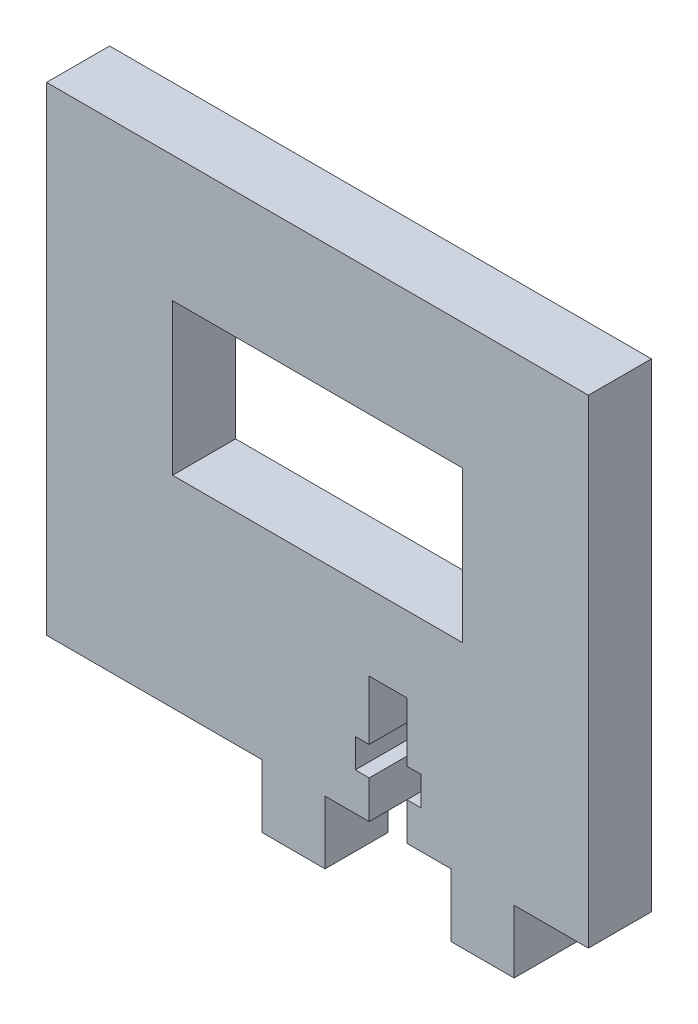
SolidWorks part; units mm, degrees
ref_plane "Front Plane" through (0, 0, 0) normal (0, 0, 1) x (1, 0, 0)
ref_plane "Top Plane" through (0, 0, 0) normal (0, 1, 0) x (1, 0, 0)
ref_plane "Right Plane" through (0, 0, 0) normal (1, 0, 0) x (0, 0, -1)
sketch "Sketch1" plane through (0, 0, 0) normal (0, 0, 1) x (1, 0, 0)
  line L0 (0, 0) -> (-15.8779, 0) construction
  line L1 (-17.1, -6) -> (5.9, -6)
  line L2 (-17.1, -6) -> (-17.1, 6)
  line L3 (-17.1, 6) -> (5.9, 6)
  line L4 (5.9, -6) -> (5.9, 6)
  line L5 (-17.1, -6) -> (5.9, 6) construction
  line L6 (-17.1, 6) -> (5.9, -6) construction
  line L7 (0, 0) -> (0, 16.675) construction
  line L10 (-27.1, -22) -> (-27.1, 16)
  line L11 (-27.1, 16) -> (15.9, 16)
  line L12 (15.9, -22) -> (15.9, 16)
  line L13 (-27.1, -22) -> (15.9, 16) construction
  line L14 (-27.1, 16) -> (15.9, -22) construction
  line L15 (-27.1, -22) -> (15.9, -22)
  circle A0 centre (0, 0) radius 5 construction
  point P0 (-5.6, 0)
  point P9 (-5.6, -3)
  line B0 (-2.6, -19) -> (-2.6, -16.7)
  line B1 (1.5, -16.7) -> (1.5, -12)
  line B2 (-1.5, -12) -> (-1.5, -16.7)
  line B3 (-2.6, -16.7) -> (-1.5, -16.7)
  line B4 (0, -22) -> (0, -10.7792) construction
  line B5 (-1.5, -22) -> (-5, -22)
  line B6 (-5, -27) -> (-10, -27)
  line B7 (-10, -27) -> (-10, -22)
  line B8 (-5, -27) -> (-5, -22)
  line B9 (1.5, -22) -> (5, -22)
  line B10 (5, -22) -> (5, -27)
  line B11 (5, -27) -> (10, -27)
  line B12 (10, -27) -> (10, -22)
  line B13 (-1.5, -22) -> (1.5, -22) construction
  line B14 (1.5, -22) -> (1.5, -19)
  line B15 (1.5, -16.7) -> (2.6, -16.7)
  line B16 (2.6, -19) -> (1.5, -19)
  line B17 (1.5, -12) -> (-1.5, -12)
  line B18 (-1.5, -19) -> (-2.6, -19)
  line B19 (2.6, -16.7) -> (2.6, -19)
  line B20 (-1.5, -19) -> (-1.5, -22)
  line B21 (0, -12) -> (0, -22) construction
  dimension "D1" = 10
  dimension "D2" = 5.9
  dimension "D3" = 17.1
  dimension "D4" = 12
  dimension "D5" = 10
  dimension "D6" = 10
  dimension "D7" = 10
  dimension "D8" = 22
sketch_block_instance "Insert M3 plots ep 5mm-4"
sketch_block "Insert M3 plots ep 5mm" parameters "D1"=10, "D2"=5, "D3"=5
sketch_block_instance "Decoupe Insert M3-4"
sketch_block "Decoupe Insert M3" parameters "D1"=5.2, "D2"=3, "D3"=2.3, "D4"=3, "D5"=10
extrude "Boss-Extrude3" add sketch "Sketch1" along normal blind 5 contours B6 B8 L15 B7 | B11 B12 L15 B10 | B20 B18 B0 B3 B2 B17 B1 B15 B19 B16 B14 L15 L12 L11 L10 L4 L1 L2 L3
